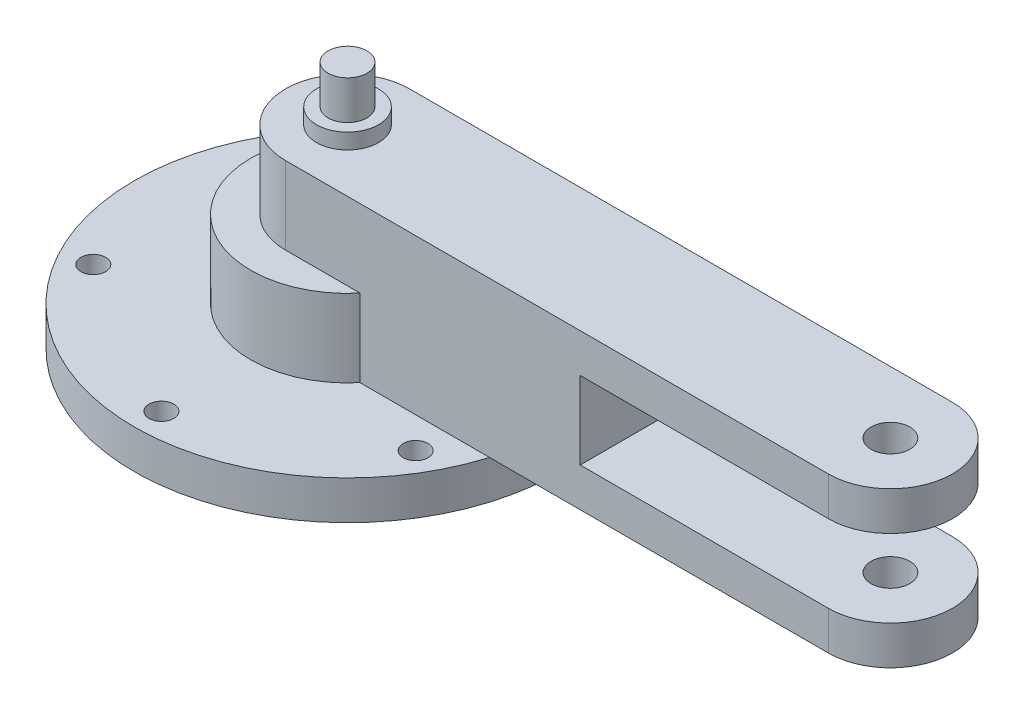
SolidWorks part; units mm, degrees
material "氧化铝"
ref_plane "前视基准面" through (0, 0, 0) normal (0, 0, 1) x (1, 0, 0)
ref_plane "上视基准面" through (0, 0, 0) normal (0, 1, 0) x (1, 0, 0)
ref_plane "右视基准面" through (0, 0, 0) normal (1, 0, 0) x (0, 0, -1)
sketch "草图2" plane through (0, 0, 0) normal (0, 1, 0) x (1, 0, 0)
  line L0 (0, 0) -> (70, 0) construction
  line L1 (0, 8) -> (70, 8)
  line L2 (0, -8) -> (70, -8)
  arc A0 (0, 8) -> (0, -8) centre (0, 0) ccw
  arc A1 (70, -8) -> (70, 8) centre (70, 0) ccw
  point P3 (35, 0)
  dimension "D1" = 8
  dimension "D2" = 70
extrude "凸台-拉伸1" add sketch "草图2" along normal mid plane 20
sketch "草图3" plane through (0, 0, 8) normal (0, 0, 1) x (1, 0, 0)
  line L0 (78, -10) -> (78, 10) construction
  line L1 (78, 5) -> (38, 5)
  line L2 (78, 5) -> (78, -5)
  line L3 (78, -5) -> (38, -5)
  line L4 (38, 5) -> (38, -5)
  point P6 (38, 0)
  dimension "D1" = 10
  dimension "D2" = 40
extrude "切除-拉伸1" cut sketch "草图3" against normal up to next
sketch "草图4" plane through (0, 10, 0) normal (0, 1, 0) x (1, 0, 0)
  circle A0 centre (70, 0) radius 2.5
  dimension "D1" = 5
extrude "切除-拉伸2" cut sketch "草图4" against normal up to surface (20 mm away) up to face at (35, -10, 0)
sketch "草图5" plane through (0, -10, 0) normal (0, -1, 0) x (1, 0, 0)
  circle A0 centre (0, 0) radius 27.5
  dimension "D1" = 55
extrude "凸台-拉伸2" add sketch "草图5" along normal blind 5
sketch "草图6" plane through (0, -10, 0) normal (0, 1, 0) x (1, 0, 0)
  circle A0 centre (0, 24) radius 1.6
  dimension "D2" = 3.2
  dimension "D1" = 24
extrude "切除-拉伸3" cut sketch "草图6" against normal up to next
pattern_circular "阵列(圆周)1" count 6 over 360 about axis through (0, 0, 0) along (0, 1, 0) of "切除-拉伸3"
sketch "草图7" plane through (0, -10, 0) normal (0, 1, 0) x (1, 0, 0)
  circle A0 centre (0, 0) radius 12.5
  dimension "D1" = 25
extrude "凸台-拉伸3" add sketch "草图7" along normal blind 10
sketch "草图8" plane through (0, 10, 0) normal (0, 1, 0) x (1, 0, 0)
  circle A0 centre (0, 0) radius 4
  dimension "D1" = 8
extrude "凸台-拉伸4" add sketch "草图8" along normal blind 2
sketch "草图9" plane through (0, 12, 0) normal (0, 1, 0) x (1, 0, 0)
  circle A0 centre (0, 0) radius 2.5
  dimension "D1" = 5
extrude "凸台-拉伸5" add sketch "草图9" along normal blind 5
sketch "草图10" plane through (0, -15, 0) normal (0, -1, 0) x (1, 0, 0)
  circle A0 centre (0, 0) radius 24
  circle A1 centre (0, 0) radius 27.5
sketch "草图11" plane through (0, -15, 0) normal (0, -1, 0) x (1, 0, 0)
